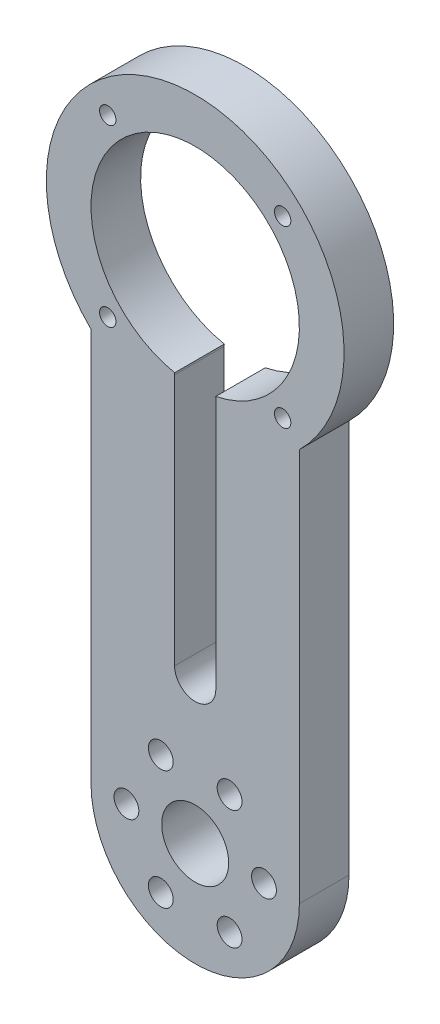
SolidWorks part; units mm, degrees
ref_plane "Front Plane" through (0, 0, 0) normal (0, 0, 1) x (1, 0, 0)
ref_plane "Top Plane" through (0, 0, 0) normal (0, 1, 0) x (1, 0, 0)
ref_plane "Right Plane" through (0, 0, 0) normal (1, 0, 0) x (0, 0, -1)
sketch "Sketch1" plane through (0, 0, 0) normal (0, 0, 1) x (1, 0, 0)
  line L0 (-0.7728, 46.7519) -> (-0.7728, -53.9487) construction
  line L1 (20.2272, 25.3276) -> (20.2272, -53.9487)
  line L2 (-21.7728, 25.3276) -> (-21.7728, -53.9487)
  line L3 (-0.7728, 25.7519) -> (-0.7728, -25.0077) construction
  line L4 (3.3812, 25.7519) -> (3.3812, -25.0077)
  line L5 (-4.9268, 25.7519) -> (-4.9268, -25.0077)
  arc A0 (20.2272, 25.3276) -> (-21.7728, 25.3276) centre (-0.7728, 46.7519) ccw
  arc A1 (3.3608, 26.1628) -> (-4.9064, 26.1628) centre (-0.7728, 46.7519) ccw
  arc A2 (-21.7728, -53.9487) -> (20.2272, -53.9487) centre (-0.7728, -53.9487) ccw
  arc A3 (3.3812, 25.7519) -> (3.3608, 26.1628) centre (-0.7728, 25.7519) ccw
  arc A4 (-4.9268, -25.0077) -> (3.3812, -25.0077) centre (-0.7728, -25.0077) ccw
  arc A5 (-4.9064, 26.1628) -> (-4.9268, 25.7519) centre (-0.7728, 25.7519) ccw
  circle A6 centre (-0.7728, -53.9487) radius 6.75
  circle A7 centre (13.0891, -53.9487) radius 2.5
  circle A8 centre (6.1582, -65.9535) radius 2.5
  circle A9 centre (-7.7038, -65.9535) radius 2.5
  circle A10 centre (-14.6347, -53.9487) radius 2.5
  circle A11 centre (-7.7038, -41.9439) radius 2.5
  circle A12 centre (6.1582, -41.9439) radius 2.5
  circle A13 centre (-18.394, 64.3731) radius 1.65
  circle A14 centre (-18.394, 29.1308) radius 1.65
  circle A15 centre (16.8484, 29.1308) radius 1.6501
  circle A16 centre (16.8484, 64.3731) radius 1.65
  point P3 (-0.7728, -3.5984)
  point P9 (-0.7728, 0.3721)
  point P33 (-0.7728, -53.9487)
extrude "Boss-Extrude2" add sketch "Sketch1" along normal blind 10
